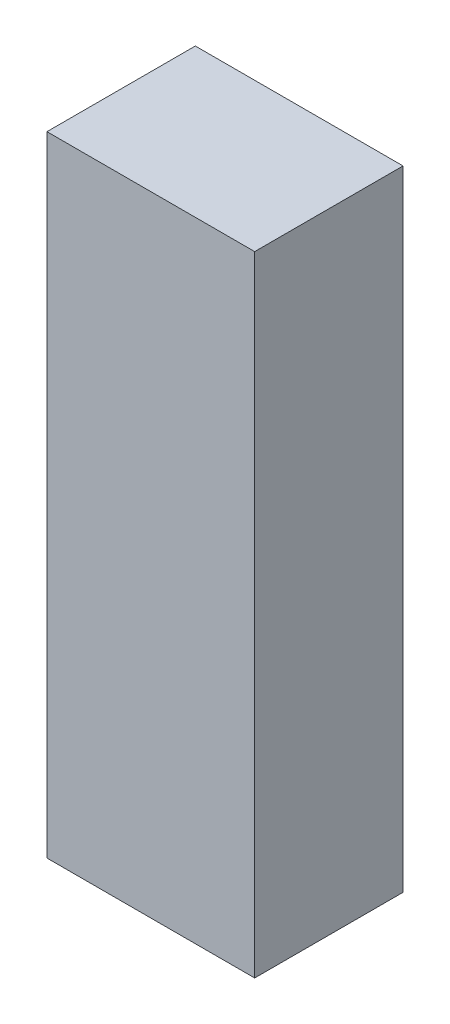
SolidWorks part; units mm, degrees
ref_plane "Front Plane" through (0, 0, 0) normal (1, 0, 0) x (0, 1, 0)
ref_plane "Top Plane" through (0, 0, 0) normal (0, 0, 1) x (0, 1, 0)
ref_plane "Right Plane" through (0, 0, 0) normal (0, 1, 0) x (-1, 0, 0)
sketch "Sketch1" plane through (0, 0, 0) normal (0, 0, 1) x (0, 1, 0)
  line L1 (-53, -17.5) -> (53, -17.5)
  line L2 (-53, -17.5) -> (-53, 17.5)
  line L3 (-53, 17.5) -> (53, 17.5)
  line L4 (53, -17.5) -> (53, 17.5)
extrude "Boss-Extrude1" add sketch "Sketch1" along normal blind 25
